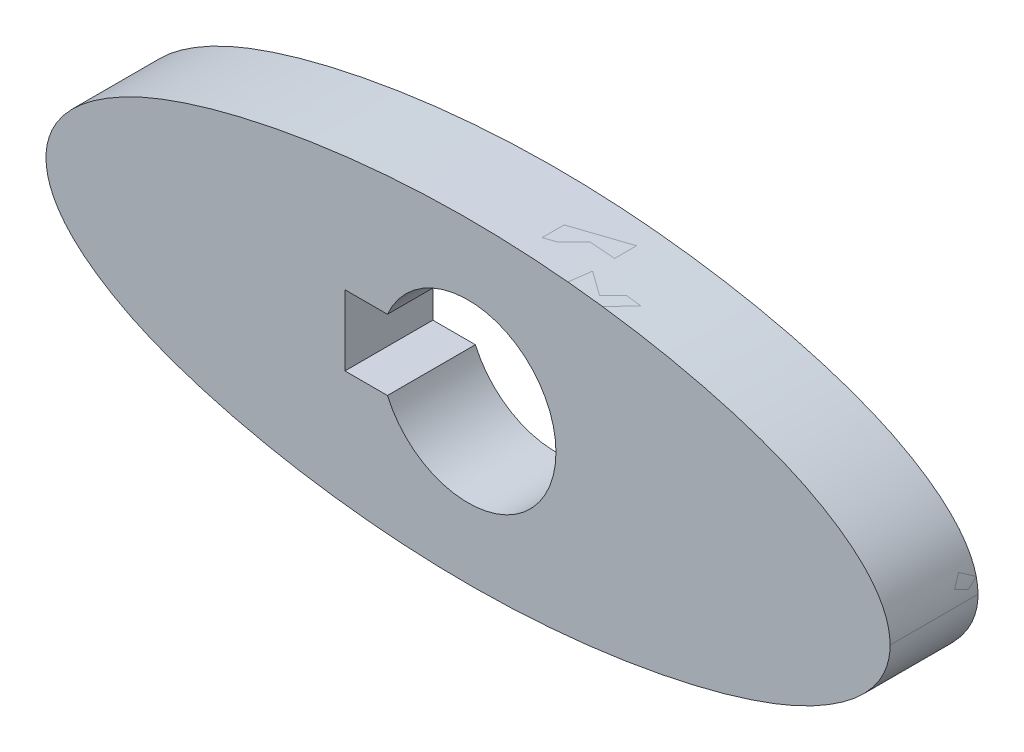
SolidWorks part; units mm, degrees
ref_plane "Alzado" through (0, 0, 0) normal (0, 0, 1) x (1, 0, 0)
ref_plane "Planta" through (0, 0, 0) normal (0, 1, 0) x (1, 0, 0)
ref_plane "Vista lateral" through (0, 0, 0) normal (1, 0, 0) x (0, 0, -1)
sketch "Croquis1" plane through (0, 0, 0) normal (0, 0, 1) x (1, 0, 0)
  line L1 (-1.0627, -3.8316) -> (1.3547, -3.8316)
  line L2 (-1.0627, -3.8316) -> (-1.0627, -7.8316)
  line L3 (-1.0627, -7.8316) -> (1.3547, -7.8316)
  arc A0 (1.3547, -3.8316) -> (1.3547, -7.8316) centre (5.9373, -5.8316) cw
  spline S0 degree 3 poles (29.9373, -5.8316) (29.9373, -4.3316) (28.9773, -2.3516) (21.2973, 1.4884) (13.9373, 3.1684) (-2.0627, 3.1684) (-9.4227, 1.4884) (-17.1027, -2.3516) (-18.0627, -4.3316) (-18.0627, -5.8316) knots 0 0 0 0 0.25 0.25 0.5 0.5 0.75 0.75 1 1 1 1
  spline S1 degree 3 poles (-18.0627, -5.8316) (-18.0627, -7.3316) (-17.1027, -9.3116) (-9.4227, -13.1516) (-2.0627, -14.8316) (13.9373, -14.8316) (21.2973, -13.1516) (28.9773, -9.3116) (29.9373, -7.3316) (29.9373, -5.8316) knots 0 0 0 0 0.25 0.25 0.5 0.5 0.75 0.75 1 1 1 1
  point P4 (-1.0627, -5.8316)
  dimension "D1" = 10
  dimension "D3" = 24
  dimension "D2" = 48
  dimension "D4" = 7
  dimension "D5" = 4
extrude "Saliente-Extruir1" add sketch "Croquis1" along normal blind 5
sketch "Croquis2" plane through (0, 0, 5) normal (0, 0, 1) x (1, 0, 0)
  spline S0 degree 3 poles (-2826.083, -1059.3685) (365.1719, 48.147) (-62.6975, 13.4858) (-9.4227, -13.1516) (-2.0627, -14.8316) (13.9373, -14.8316) (21.2973, -13.1516) (74.572, 13.4857) (-353.2962, 48.1469) (2837.9444, -1059.3639) knots -2.96841 -2.96841 -2.96841 -2.96841 0.25 0.25 0.5 0.5 0.75 0.75 3.968406 3.968406 3.968406 3.968406 only from (-18.0627, -5.8316) to (29.9373, -5.8316) construction
  spline S1 degree 3 poles (2837.9575, 1047.7052) (-353.2974, -59.8103) (74.5721, -25.149) (21.2973, 1.4884) (13.9373, 3.1684) (-2.0627, 3.1684) (-9.4227, 1.4884) (-62.6974, -25.149) (365.1707, -59.8102) (-2826.0698, 1047.7006) knots -2.96841 -2.96841 -2.96841 -2.96841 0.25 0.25 0.5 0.5 0.75 0.75 3.968406 3.968406 3.968406 3.968406 only from (29.9373, -5.8316) to (-18.0627, -5.8316) construction
  spline S2 degree 3 poles (-18.0627, -5.8316) (-18.0627, -7.3316) (-17.1027, -9.3116) (-9.4227, -13.1516) (-2.0627, -14.8316) (13.9373, -14.8316) (21.2973, -13.1516) (28.9773, -9.3116) (29.9373, -7.3316) (29.9373, -5.8316) knots 0 0 0 0 0.25 0.25 0.5 0.5 0.75 0.75 1 1 1 1
  spline S3 degree 3 poles (29.9373, -5.8316) (29.9373, -4.3316) (28.9773, -2.3516) (21.2973, 1.4884) (13.9373, 3.1684) (-2.0627, 3.1684) (-9.4227, 1.4884) (-17.1027, -2.3516) (-18.0627, -4.3316) (-18.0627, -5.8316) knots 0 0 0 0 0.25 0.25 0.5 0.5 0.75 0.75 1 1 1 1
surface "Superficie-Extruir1" sketch "Croquis2" parameters "D1"=5
